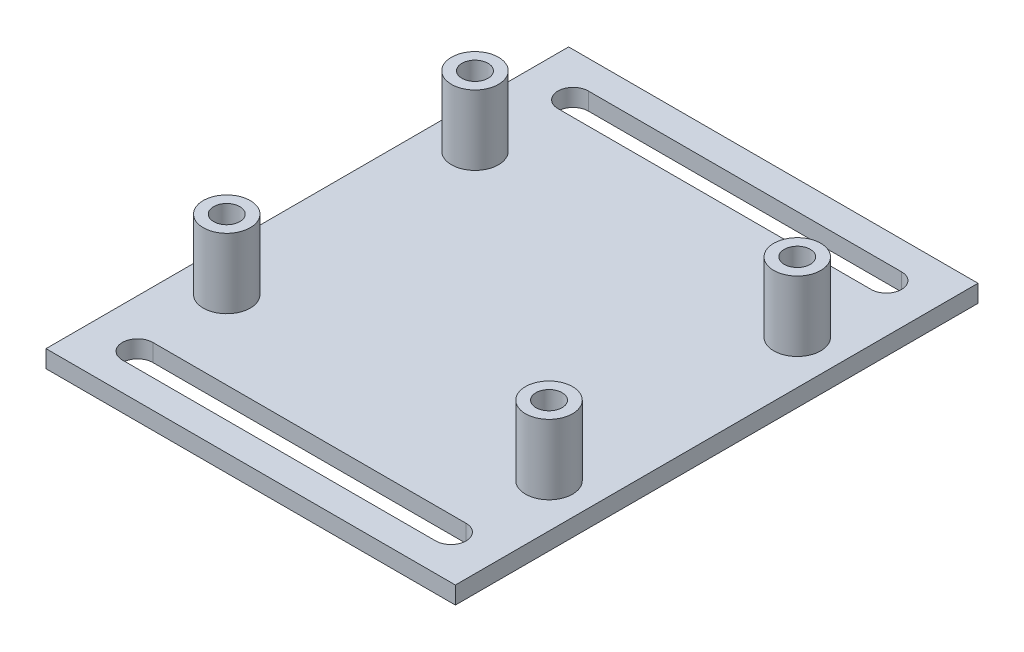
SolidWorks part; units mm, degrees
ref_plane "Front Plane" through (0, 0, 0) normal (0, 0, 1) x (1, 0, 0)
ref_plane "Top Plane" through (0, 0, 0) normal (0, 1, 0) x (1, 0, 0)
ref_plane "Right Plane" through (0, 0, 0) normal (1, 0, 0) x (0, 0, -1)
sketch "Sketch1" plane through (0, 0, 0) normal (0, 1, 0) x (1, 0, 0)
  line L0 (-17.9824, 25) -> (17.9824, 25) construction
  line L1 (-23.5, 30) -> (23.5, 30)
  line L2 (-23.5, 30) -> (-23.5, -30)
  line L3 (-23.5, -30) -> (23.5, -30)
  line L4 (23.5, 30) -> (23.5, -30)
  line L5 (-23.5, 30) -> (23.5, -30) construction
  line L6 (-23.5, -30) -> (23.5, 30) construction
  line L7 (-17.9824, 26.75) -> (17.9824, 26.75)
  line L8 (-17.9824, 23.25) -> (17.9824, 23.25)
  line L9 (-17.9824, -25) -> (17.9824, -25) construction
  line L10 (-17.9824, -23.25) -> (17.9824, -23.25)
  line L11 (-17.9824, -26.75) -> (17.9824, -26.75)
  line L12 (0, 25) -> (0, 0) construction
  line L13 (0, 0) -> (0, -25) construction
  arc A0 (-17.9824, 26.75) -> (-17.9824, 23.25) centre (-17.9824, 25) ccw
  arc A1 (17.9824, 23.25) -> (17.9824, 26.75) centre (17.9824, 25) ccw
  arc A2 (-17.9824, -23.25) -> (-17.9824, -26.75) centre (-17.9824, -25) ccw
  arc A3 (17.9824, -26.75) -> (17.9824, -23.25) centre (17.9824, -25) ccw
  point P0 (0, 0)
  point P8 (0, 25)
  point P13 (0, -25)
  dimension "D3" = 1.75
  dimension "D1" = 60
  dimension "D2" = 47
  dimension "D4" = 5
extrude "Boss-Extrude1" add sketch "Sketch1" along normal blind 2
sketch "Sketch2" plane through (0, 2, 0) normal (0, 1, 0) x (1, 0, 0)
  line L0 (-18.5, 14.25) -> (18.5, 14.25) construction
  line L1 (18.5, 14.25) -> (18.5, -14.25) construction
  line L2 (18.5, -14.25) -> (-18.5, -14.25) construction
  line L3 (0, 14.25) -> (0, 0) construction
  line L4 (-23.5, 19.25) -> (-13.5, 19.25) construction
  line L5 (-23.5, 19.25) -> (-23.5, 9.25) construction
  line L6 (-23.5, 9.25) -> (-13.5, 9.25) construction
  line L7 (-13.5, 19.25) -> (-13.5, 9.25) construction
  line L8 (-23.5, 19.25) -> (-13.5, 9.25) construction
  line L9 (-23.5, 9.25) -> (-13.5, 19.25) construction
  line L10 (13.5, 19.25) -> (23.5, 19.25) construction
  line L11 (13.5, 19.25) -> (13.5, 9.25) construction
  line L12 (13.5, 9.25) -> (23.5, 9.25) construction
  line L13 (23.5, 19.25) -> (23.5, 9.25) construction
  line L14 (13.5, 19.25) -> (23.5, 9.25) construction
  line L15 (13.5, 9.25) -> (23.5, 19.25) construction
  line L16 (23.5, -19.25) -> (13.5, -19.25) construction
  line L17 (23.5, -19.25) -> (23.5, -9.25) construction
  line L18 (23.5, -9.25) -> (13.5, -9.25) construction
  line L19 (13.5, -19.25) -> (13.5, -9.25) construction
  line L20 (23.5, -19.25) -> (13.5, -9.25) construction
  line L21 (23.5, -9.25) -> (13.5, -19.25) construction
  line L22 (-23.5, -19.25) -> (-13.5, -19.25) construction
  line L23 (-23.5, -19.25) -> (-23.5, -9.25) construction
  line L24 (-23.5, -9.25) -> (-13.5, -9.25) construction
  line L25 (-13.5, -19.25) -> (-13.5, -9.25) construction
  line L26 (-23.5, -19.25) -> (-13.5, -9.25) construction
  line L27 (-23.5, -9.25) -> (-13.5, -19.25) construction
  line L28 (0, 0) -> (18.5, 0) construction
  circle A0 centre (-18.5, 14.25) radius 1.5
  circle A1 centre (18.5, 14.25) radius 1.5
  circle A2 centre (18.5, -14.25) radius 1.5
  circle A3 centre (-18.5, -14.25) radius 1.5
  circle A4 centre (-18.5, 14.25) radius 2.7
  circle A5 centre (18.5, 14.25) radius 2.7
  circle A6 centre (18.5, -14.25) radius 2.7
  circle A7 centre (-18.5, -14.25) radius 2.7
  dimension "D1" = 3
  dimension "D2" = 10
  dimension "D3" = 37
  dimension "D4" = 28.5
  dimension "D5" = 1.2
extrude "Boss-Extrude2" add sketch "Sketch2" along normal blind 8
equation "\"h\"= 60"
equation "\"D1@Sketch1\"=\"h\""
equation "\"w\"= 47"
equation "\"D2@Sketch1\"=\"w\""
equation "\"pcb_hole_w\"= 37"
equation "\"D3@Sketch2\"=\"pcb_hole_w\""
equation "\"pcb_hole_h\"=28.5"
equation "\"D4@Sketch2\"=\"pcb_hole_h\""
equation "\"slot_r\"=1.75"
equation "\"D3@Sketch1\"=\"slot_r\""
equation "\"slot_border\"=5"
equation "\"D4@Sketch1\"=\"slot_border\""
